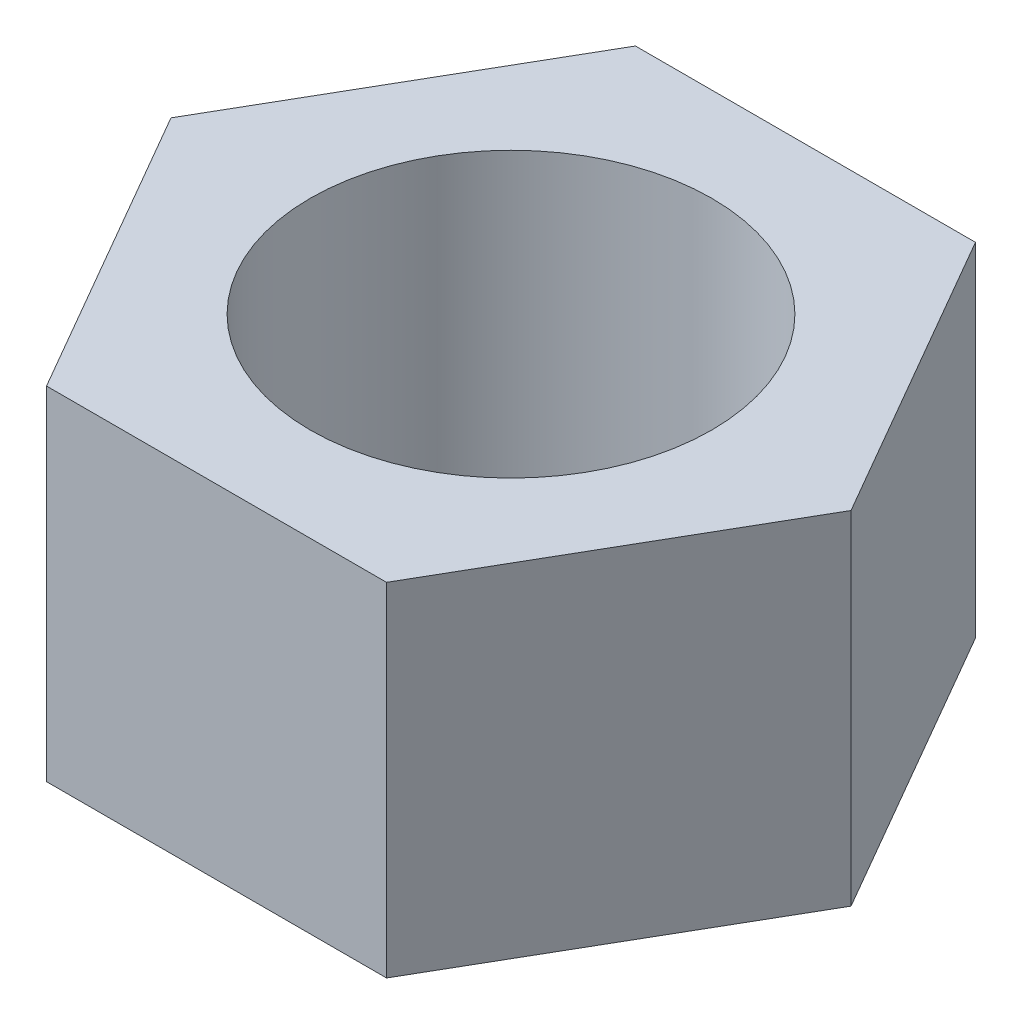
SolidWorks part; units mm, degrees
ref_plane "Front Plane" through (0, 0, 0) normal (0, 0, 1) x (1, 0, 0)
ref_plane "Top Plane" through (0, 0, 0) normal (0, 1, 0) x (1, 0, 0)
ref_plane "Right Plane" through (0, 0, 0) normal (1, 0, 0) x (0, 0, -1)
sketch "Sketch1" plane through (0, 0, 0) normal (0, 1, 0) x (1, 0, 0)
  line L1 (8.0656, 13.97) -> (-8.0656, 13.97)
  line L2 (-8.0656, 13.97) -> (-16.1312, 0)
  line L3 (-16.1312, 0) -> (-8.0656, -13.97)
  line L4 (-8.0656, -13.97) -> (8.0656, -13.97)
  line L5 (8.0656, -13.97) -> (16.1312, 0)
  line L6 (16.1312, 0) -> (8.0656, 13.97)
  circle A0 centre (0, 0) radius 13.97 construction
  circle A1 centre (0, 0) radius 9.525
  dimension "D2" = 19.05
  dimension "D1" = 27.94
extrude "Boss-Extrude1" add sketch "Sketch1" along normal blind 16.256
